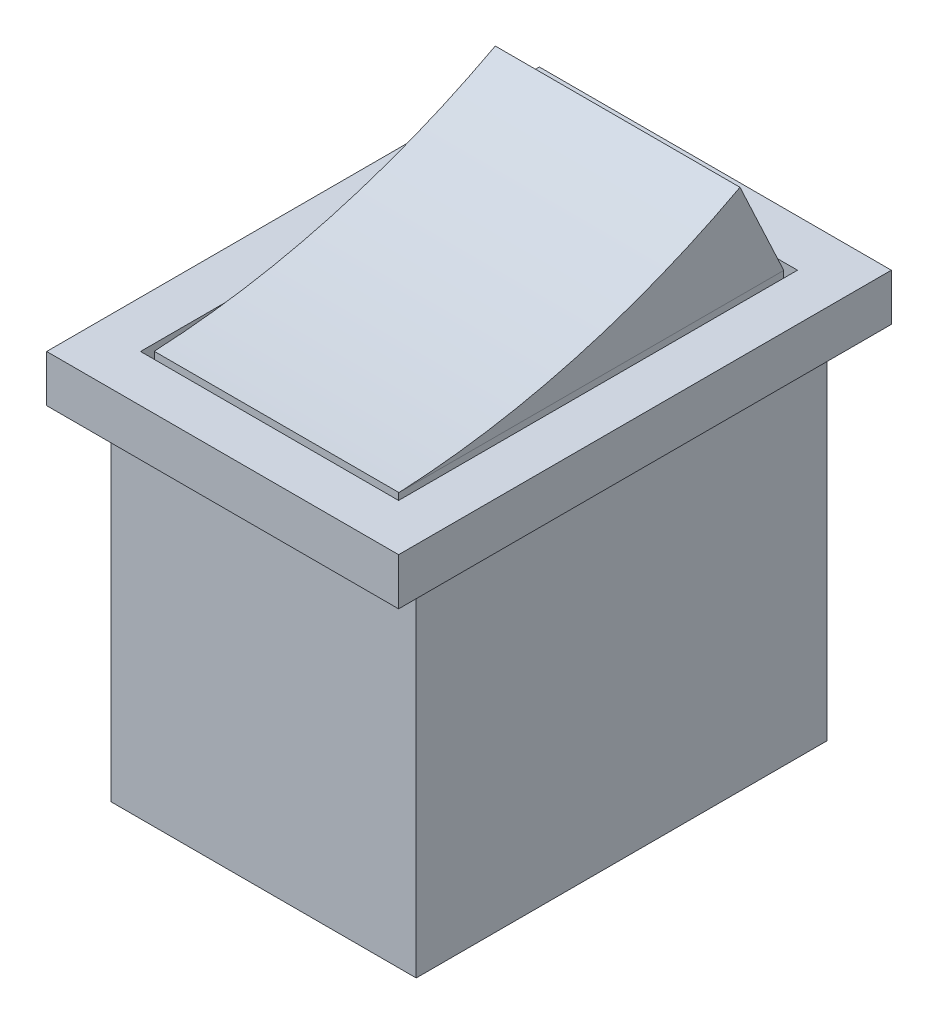
SolidWorks part; units mm, degrees
ref_plane "前视基准面" through (0, 0, 0) normal (0, 0, 1) x (1, 0, 0)
ref_plane "上视基准面" through (0, 0, 0) normal (0, 1, 0) x (1, 0, 0)
ref_plane "右视基准面" through (0, 0, 0) normal (1, 0, 0) x (0, 0, -1)
sketch "草图1" plane through (0, 0, 0) normal (0, 1, 0) x (1, 0, 0)
  line L1 (-6.5, -8.75) -> (6.5, -8.75)
  line L2 (-6.5, -8.75) -> (-6.5, 8.75)
  line L3 (-6.5, 8.75) -> (6.5, 8.75)
  line L4 (6.5, -8.75) -> (6.5, 8.75)
  line L5 (-6.5, -8.75) -> (6.5, 8.75) construction
  line L6 (-6.5, 8.75) -> (6.5, -8.75) construction
  point P0 (0, 0)
  dimension "D1" = 13
  dimension "D2" = 17.5
extrude "凸台-拉伸1" add sketch "草图1" along normal blind 15
sketch "草图2" plane through (0, 15, 0) normal (0, 1, 0) x (1, 0, 0)
  line L1 (-7.5, -10.5) -> (7.5, -10.5)
  line L2 (-7.5, -10.5) -> (-7.5, 10.5)
  line L3 (-7.5, 10.5) -> (7.5, 10.5)
  line L4 (7.5, -10.5) -> (7.5, 10.5)
  line L5 (-7.5, -10.5) -> (7.5, 10.5) construction
  line L6 (-7.5, 10.5) -> (7.5, -10.5) construction
  point P0 (0, 0)
  dimension "D1" = 15
  dimension "D2" = 21
extrude "凸台-拉伸2" add sketch "草图2" along normal blind 2
sketch "草图3" plane through (0, 17, 0) normal (0, 1, 0) x (1, 0, 0)
  line L3 (-5.2, 8.2) -> (-5.2, -8.2)
  line L4 (-5.2, -8.2) -> (5.2, -8.2)
  line L14 (5.2, -8.2) -> (5.2, 8.2)
  line L15 (5.2, 8.2) -> (-5.2, 8.2)
  line L18 (5.5, 8.5) -> (-5.5, 8.5)
  line L19 (-5.5, -8.5) -> (5.5, -8.5)
  line L20 (5.5, -8.5) -> (5.5, 8.5)
  line L21 (-5.5, 8.5) -> (-5.5, -8.5)
  line L22 (5.5, 8.5) -> (-5.5, 8.5)
  line L23 (-5.5, -8.5) -> (5.5, -8.5)
  line L24 (5.5, -8.5) -> (5.5, 8.5)
  line L25 (-5.5, 8.5) -> (-5.5, -8.5)
  dimension "D1" = 0.3
  dimension "D2" = 2
extrude "切除-拉伸1" cut sketch "草图3" against normal blind 3
sketch "草图4" plane through (0, 0, 0) normal (1, 0, 0) x (0, 0, -1)
  line L0 (8.2, 17) -> (6.3348, 21)
  line L2 (-8.2, 17) -> (8.2, 17)
  line L3 (5.1393, 21) -> (7.7746, 21) construction
  line L4 (10.5, 17) -> (-10.5, 17) construction
  arc A0 (6.3348, 21) -> (-8.2, 17) centre (-9.8447, 51.3836) cw
  dimension "D3" = 4
  dimension "D2" = 65
extrude "凸台-拉伸3" add sketch "草图4" along normal mid plane 10.43 separate body
